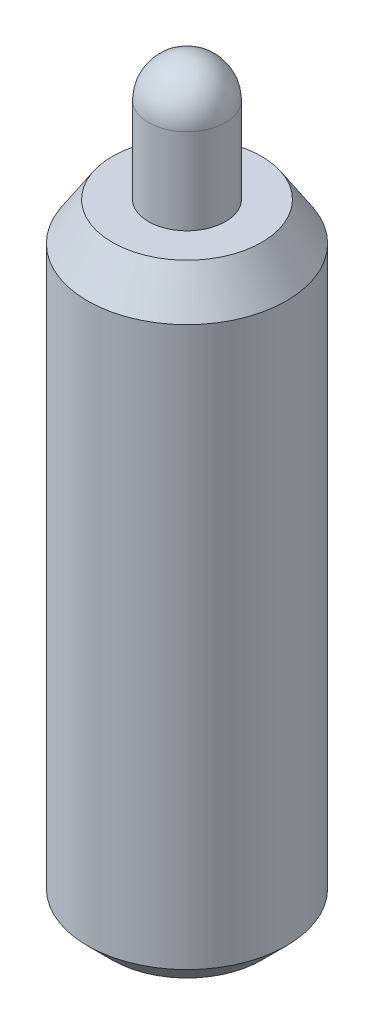
SolidWorks part; units mm, degrees
ref_plane "前视基准面" through (0, 0, 0) normal (0, 0, 1) x (1, 0, 0)
ref_plane "上视基准面" through (0, 0, 0) normal (0, 1, 0) x (1, 0, 0)
ref_plane "右视基准面" through (0, 0, 0) normal (1, 0, 0) x (0, 0, -1)
sketch "草图1" plane through (0, 0, 0) normal (1, 0, 0) x (0, 0, -1)
  line L0 (0, 46.2984) -> (0, -39.6162) construction
  line L1 (-16.4783, 0) -> (19.9104, 0) construction
  line L2 (-3, 0) -> (-1.55, 0)
  line L3 (-4, -1.5367) -> (-4, -24)
  line L4 (-4, -24) -> (-3, -25)
  line L5 (-3, -25) -> (0, -25)
  line L6 (0, 5) -> (0, -25)
  line L7 (-1.55, 0) -> (-1.55, 3.45)
  line L8 (-6.314, 5) -> (5.8117, 5) construction
  line L9 (-3.3633, 3.45) -> (1.7013, 3.45) construction
  line L10 (-3, 0) -> (-4, -1.5367)
  arc A0 (0, 5) -> (-1.55, 3.45) centre (0, 3.45) ccw
  point P6 (-4, 0)
  point P14 (-3.9792, -1.5048)
  dimension "D5" = 1.55
  dimension "D2" = 4
  dimension "D3" = 1
  dimension "D6" = 1
revolve "旋转1" add sketch "草图1" angle 360 about L0
